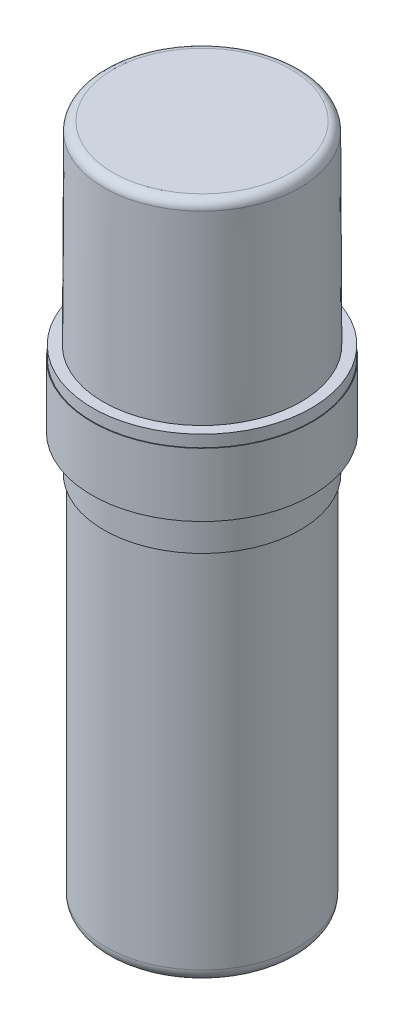
SolidWorks part; units mm, degrees
ref_plane "Front Plane" through (0, 0, 0) normal (0, 0, 1) x (1, 0, 0)
ref_plane "Top Plane" through (0, 0, 0) normal (0, 1, 0) x (1, 0, 0)
ref_plane "Right Plane" through (0, 0, 0) normal (1, 0, 0) x (0, 0, -1)
sketch "Sketch1" plane through (0, 0, 0) normal (0, 0, 1) x (1, 0, 0)
  line L0 (0, 0) -> (0, 154.2)
  line L1 (0, 0) -> (21.75, 0)
  line L2 (21.75, 0) -> (21.75, 85.09)
  line L3 (21.75, 85.09) -> (22.25, 85.09)
  line L4 (22.25, 85.09) -> (22.25, 93.26)
  line L5 (22.25, 93.26) -> (24.95, 93.26)
  line L6 (24.95, 93.26) -> (24.95, 107.63)
  line L7 (24.95, 107.63) -> (24.8, 107.63)
  line L8 (24.8, 107.63) -> (24.8, 110.3)
  line L9 (24.8, 110.3) -> (22.4, 110.3)
  line L12 (22.4, 110.3) -> (22.2, 154.2)
  line L13 (22.2, 154.2) -> (0, 154.2)
  point P9 (38.6415, 110.6156)
  point P13 (0, 150.2797)
  point P14 (22.8006, 110.3)
  point P16 (35.4121, 147.9323)
  point P17 (10.3953, 147.5884)
  dimension "D1" = 21.75
  dimension "D2" = 85.09
  dimension "D3" = 22.25
  dimension "D4" = 93.26
  dimension "D5" = 14.37
  dimension "D6" = 24.95
  dimension "D7" = 24.8
  dimension "D8" = 110.3
  dimension "D9" = 154.2
  dimension "D10" = 22.2
  dimension "D11" = 22.4
revolve "Revolve1" add sketch "Sketch1" angle 360 about L0
fillet "Fillet1" radius 2 1 edges at (0, 154.2, -22.2)
fillet "Fillet2" radius 3 1 edges at (0, 0, -21.75)
